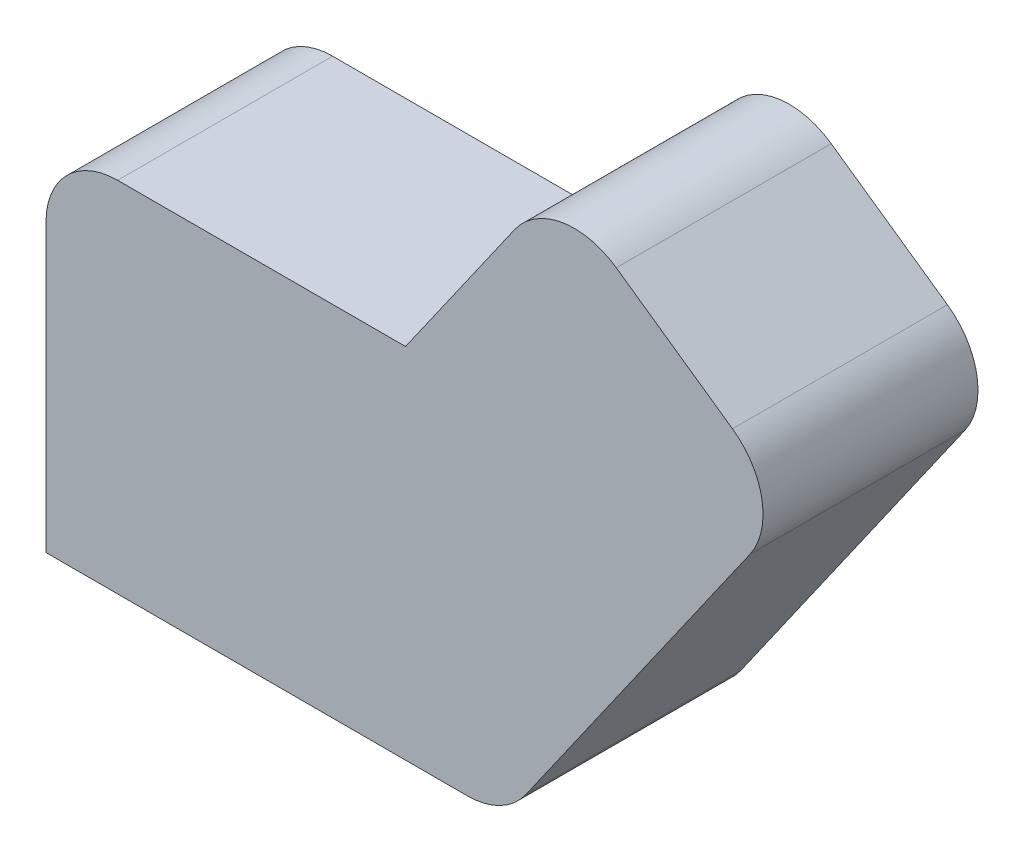
SolidWorks part; units mm, degrees
ref_plane "정면" through (0, 0, 0) normal (0, 0, 1) x (1, 0, 0)
ref_plane "윗면" through (0, 0, 0) normal (0, 1, 0) x (1, 0, 0)
ref_plane "우측면" through (0, 0, 0) normal (1, 0, 0) x (0, 0, -1)
sketch "스케치1" plane through (0, 0, 0) normal (0, 0, 1) x (1, 0, 0)
  line L0 (0, 0) -> (32, 0)
  line L1 (32, 0) -> (52, 28.563)
  line L2 (52, 28.563) -> (35.617, 40.0345)
  line L3 (35.617, 40.0345) -> (25.0897, 25)
  line L4 (25.0897, 25) -> (0, 25)
  line L5 (0, 25) -> (0, 0)
  dimension "D1" = 32
  dimension "D2" = 52
  dimension "D3" = 20
  dimension "D4" = 25
  dimension "D5" = 125
extrude "보스-돌출1" add sketch "스케치1" along normal blind 15
fillet "필렛1" radius 5.1 1 edges at (35.617, 40.0345, 7.5)
fillet "필렛2" radius 5 1 edges at (32, 0, 7.5)
fillet "필렛3" radius 5 1 edges at (0, 25, 7.5)
fillet "필렛4" radius 5 1 edges at (52, 28.563, 7.5)
